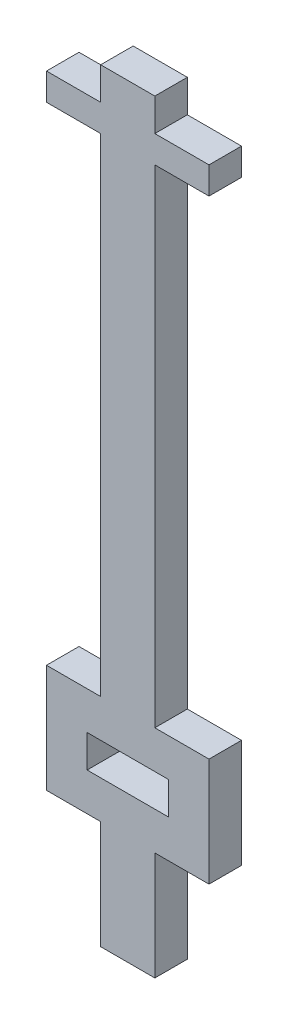
SolidWorks part; units mm, degrees
ref_plane "Front Plane" through (0, 0, 0) normal (0, 0, 1) x (1, 0, 0)
ref_plane "Top Plane" through (0, 0, 0) normal (0, 1, 0) x (1, 0, 0)
ref_plane "Right Plane" through (0, 0, 0) normal (1, 0, 0) x (0, 0, -1)
sketch "Sketch1" plane through (0, 0, 0) normal (0, 0, 1) x (1, 0, 0)
  line L0 (0, 0) -> (12.7, 0)
  line L5 (12.7, 165.1) -> (25.4, 165.1)
  line L6 (25.4, 165.1) -> (25.4, 171.45)
  line L7 (25.4, 171.45) -> (12.7, 171.45)
  line L8 (12.7, 171.45) -> (12.7, 179.07)
  line L9 (12.7, 179.07) -> (0, 179.07)
  line L10 (0, 179.07) -> (0, 171.45)
  line L11 (0, 171.45) -> (-12.7, 171.45)
  line L16 (-12.7, 171.45) -> (-12.7, 165.1)
  line L17 (-12.7, 165.1) -> (0, 165.1)
  line L18 (0, 165.1) -> (0, 0)
  line L19 (12.7, 0) -> (12.7, 165.1)
  dimension "D1" = 7.62
  dimension "D2" = 6.35
  dimension "D3" = 12.7
  dimension "D4" = 12.7
  dimension "D5" = 165.1
extrude "Boss-Extrude1" add sketch "Sketch1" along normal blind 7.62
sketch "Sketch2" plane through (0, 0, 0) normal (-1, 0, 0) x (0, 0, 1)
  line L0 (3.81, 0) -> (3.81, 38.1) construction
  line L1 (7.62, 0) -> (0, 0) construction
  line L2 (7.62, 165.1) -> (7.62, 0) construction
  line L3 (0, 50.8) -> (7.62, 50.8)
  line L4 (0, 50.8) -> (0, 25.4)
  line L5 (0, 25.4) -> (7.62, 25.4)
  line L6 (7.62, 50.8) -> (7.62, 25.4)
  line L7 (0, 50.8) -> (7.62, 25.4) construction
  line L8 (0, 25.4) -> (7.62, 50.8) construction
  dimension "D1" = 38.1
  dimension "D2" = 25.4
extrude "Boss-Extrude2" add sketch "Sketch2" along normal blind 12.7 and the other way blind 25.4
sketch "Sketch3" plane through (0, 0, 7.62) normal (0, 0, 1) x (1, 0, 0)
  line L0 (6.35, 0) -> (6.35, 38.1) construction
  line L1 (0, 0) -> (12.7, 0) construction
  line L3 (-3.175, 34.29) -> (15.875, 34.29)
  line L4 (-3.175, 34.29) -> (-3.175, 41.91)
  line L5 (-3.175, 41.91) -> (15.875, 41.91)
  line L6 (15.875, 34.29) -> (15.875, 41.91)
  line L7 (-3.175, 34.29) -> (15.875, 41.91) construction
  line L8 (-3.175, 41.91) -> (15.875, 34.29) construction
  dimension "D1" = 38.1
  dimension "D2" = 19.05
  dimension "D3" = 7.62
extrude "Cut-Extrude1" cut sketch "Sketch3" against normal through all
equation "\"Foamcore\" = .1in"
equation "\"MDF\" = .3in"
equation "\"Gmaterial\"= \"MDF\""
equation "\"PVC-ID\" = \"1.590in\""
equation "\"PVC-OD\" = \"1.900in\""
equation "\"PVC-Sleeve-Width\" = \".51in\""
equation "\"D1@Sketch1\"=\"Gmaterial\""
equation "\"D1@Boss-Extrude1\"=\"Gmaterial\""
equation "\"D2@Boss-Extrude2\"=1"
equation "\"D3@Sketch3\"=\"Gmaterial\""
